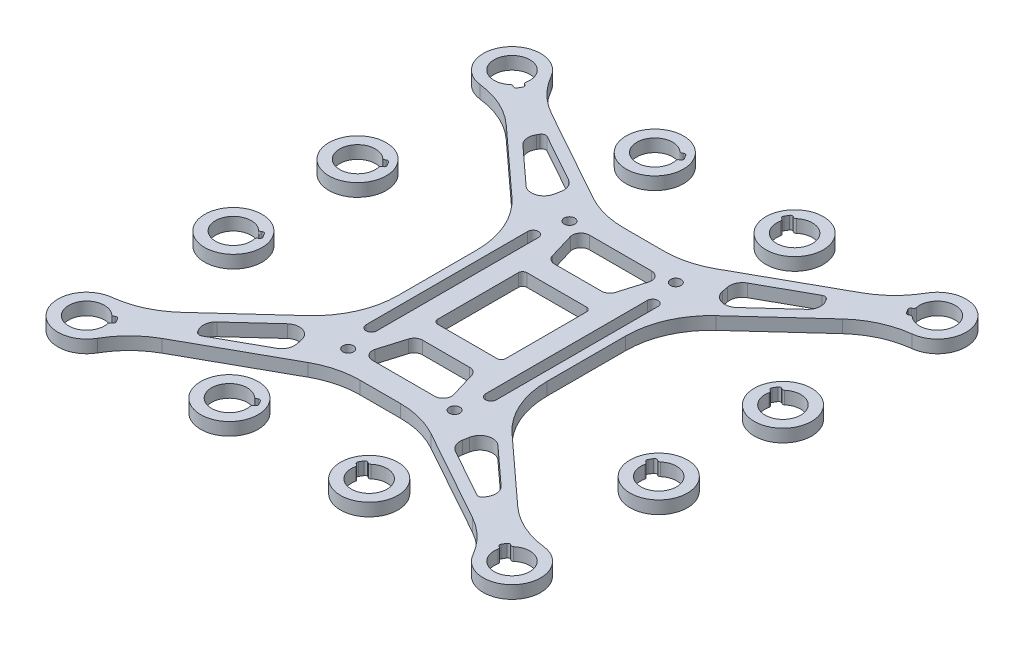
SolidWorks part; units mm, degrees
ref_plane "Front Plane" through (0, 0, 0) normal (0, 0, 1) x (1, 0, 0)
ref_plane "Top Plane" through (0, 0, 0) normal (0, 1, 0) x (1, 0, 0)
ref_plane "Right Plane" through (0, 0, 0) normal (1, 0, 0) x (0, 0, -1)
sketch "Sketch1" plane through (0, 0, 0) normal (0, 1, 0) x (1, 0, 0)
  line L0 (17.5, 31) -> (50, 50) construction
  line L1 (-50, 50) -> (50, 50) construction
  line L2 (-50, 50) -> (-50, -50) construction
  line L3 (-50, -50) -> (50, -50) construction
  line L4 (50, 50) -> (50, -50) construction
  line L5 (0, -50) -> (0, 50) construction
  line L6 (-50, 0) -> (50, 0) construction
  line L7 (-17.5, 31) -> (17.5, 31) construction
  line L8 (-17.5, 31) -> (-17.5, -31) construction
  line L9 (-17.5, -31) -> (17.5, -31) construction
  line L10 (17.5, 31) -> (17.5, -31) construction
  line L11 (0, -31) -> (0, 31) construction
  line L12 (-17.5, 0) -> (17.5, 0) construction
  line L13 (50, -50) -> (17.5, -31) construction
  line L14 (24.0097, -23.9982) -> (39.5398, -38.1874)
  line L15 (14.4627, -33.5209) -> (36.4779, -45.7634)
  line L16 (17.5, -18.0505) -> (9.9296, -31) construction
  line L17 (46.294, -44.3584) -> (43.2658, -49.5381) construction
  line L18 (17.5, -31) -> (11.8579, -27.7015) construction
  line L19 (-4.7426, -31) -> (4.7426, -31)
  line L20 (17.5, -9.233) -> (17.5, 9.233)
  line L21 (24.0097, 23.9982) -> (39.5398, 38.1874)
  line L22 (14.4627, 33.5209) -> (36.4779, 45.7634)
  line L23 (-4.7426, 31) -> (4.7426, 31)
  line L24 (-14.4627, 33.5209) -> (-36.4779, 45.7634)
  line L25 (-24.0097, 23.9982) -> (-39.5398, 38.1874)
  line L26 (-17.5, -9.233) -> (-17.5, 9.233)
  line L27 (-24.0097, -23.9982) -> (-39.5398, -38.1874)
  line L28 (-14.4627, -33.5209) -> (-36.4779, -45.7634)
  line L29 (-14.05, 19) -> (-14.05, -19) construction
  line L30 (-15.3, -28.5) -> (15.3, -28.5) construction
  line L31 (-15.3, -28.5) -> (-15.3, 28.5) construction
  line L32 (-15.3, 28.5) -> (15.3, 28.5) construction
  line L33 (15.3, -28.5) -> (15.3, 28.5) construction
  line L34 (0, 28.5) -> (0, -28.5) construction
  line L35 (-15.3, 0) -> (15.3, 0) construction
  line L36 (-12.8, 19) -> (-12.8, -19)
  line L37 (-15.3, 19) -> (-15.3, -19)
  line L38 (14.05, 19) -> (14.05, -19) construction
  line L39 (-7, -10.5) -> (7, -10.5)
  line L40 (-8, -9.5) -> (-8, 9.5)
  line L41 (-7, 10.5) -> (7, 10.5)
  line L42 (8, -9.5) -> (8, 9.5)
  line L43 (0, 10.5) -> (0, -10.5) construction
  line L44 (-8, 0) -> (8, 0) construction
  line L45 (12.8, 19) -> (12.8, -19)
  line L46 (15.3, 19) -> (15.3, -19)
  line L47 (21.0169, -34.3051) -> (32.3084, -40.5842)
  line L48 (33.6577, -40.215) -> (33.9641, -39.6909)
  line L49 (33.3978, -35.962) -> (24.7539, -28.0645)
  line L50 (19.7788, -29.7423) -> (19.5234, -31.1462)
  line L51 (19.7788, 29.7423) -> (19.5234, 31.1462)
  line L52 (33.3978, 35.962) -> (24.7539, 28.0645)
  line L53 (33.6577, 40.215) -> (33.9641, 39.6909)
  line L54 (21.0169, 34.3051) -> (32.3084, 40.5842)
  line L55 (-33.6577, -40.215) -> (-33.9641, -39.6909)
  line L56 (-21.0169, -34.3051) -> (-32.3084, -40.5842)
  line L57 (-33.3978, -35.962) -> (-24.7539, -28.0645)
  line L58 (-19.7788, -29.7423) -> (-19.5234, -31.1462)
  line L59 (-19.7788, 29.7423) -> (-19.5234, 31.1462)
  line L60 (-33.3978, 35.962) -> (-24.7539, 28.0645)
  line L61 (-33.6577, 40.215) -> (-33.9641, 39.6909)
  line L62 (-21.0169, 34.3051) -> (-32.3084, 40.5842)
  line L63 (-5.5119, 15.5) -> (5.5119, 15.5)
  line L64 (7.4276, 16.9253) -> (9.2276, 22.9253)
  line L65 (7.3119, 25.5) -> (-7.3119, 25.5)
  line L66 (-7.4276, 16.9253) -> (-9.2276, 22.9253)
  line L67 (-7.4276, -16.9253) -> (-9.2276, -22.9253)
  line L68 (7.4276, -16.9253) -> (9.2276, -22.9253)
  line L69 (7.3119, -25.5) -> (-7.3119, -25.5)
  line L70 (-5.5119, -15.5) -> (5.5119, -15.5)
  line L71 (45.7632, -46.9439) -> (45.2585, -47.8072)
  line L72 (46.4472, -46.7646) -> (46.6594, -46.8887)
  line L73 (45.4378, -48.4912) -> (45.65, -48.6153)
  line L74 (-45.7632, -46.9439) -> (-45.2585, -47.8072)
  line L75 (-45.4378, -48.4912) -> (-45.65, -48.6153)
  line L76 (-46.4472, -46.7646) -> (-46.6594, -46.8887)
  line L77 (45.7632, 46.9439) -> (45.2585, 47.8072)
  line L78 (45.4378, 48.4912) -> (45.65, 48.6153)
  line L79 (46.4472, 46.7646) -> (46.6594, 46.8887)
  line L80 (-45.7632, 46.9439) -> (-45.2585, 47.8072)
  line L81 (-46.4472, 46.7646) -> (-46.6594, 46.8887)
  line L82 (-45.4378, 48.4912) -> (-45.65, 48.6153)
  line L83 (46.4472, -12.2646) -> (46.6594, -12.3887)
  line L84 (45.7632, -12.4439) -> (45.2585, -13.3072)
  line L85 (45.4378, -13.9912) -> (45.65, -14.1153)
  line L86 (45.7632, 16.7469) -> (45.2585, 15.8836)
  line L87 (45.4378, 15.1996) -> (45.65, 15.0756)
  line L88 (46.4472, 16.9262) -> (46.6594, 16.8022)
  line L89 (-45.4378, -13.9912) -> (-45.65, -14.1153)
  line L90 (-45.7632, -12.4439) -> (-45.2585, -13.3072)
  line L91 (-46.4472, -12.2646) -> (-46.6594, -12.3887)
  line L92 (-46.4472, 16.9262) -> (-46.6594, 16.8022)
  line L93 (-45.4378, 15.1996) -> (-45.65, 15.0756)
  line L94 (-45.7632, 16.7469) -> (-45.2585, 15.8836)
  line L95 (12.1942, 53.0561) -> (11.6896, 52.1928)
  line L96 (12.8782, 53.2354) -> (13.0904, 53.1113)
  line L97 (11.8689, 51.5088) -> (12.081, 51.3847)
  line L98 (12.1942, -46.9439) -> (11.6896, -47.8072)
  line L99 (11.8689, -48.4912) -> (12.081, -48.6153)
  line L100 (12.8782, -46.7646) -> (13.0904, -46.8887)
  line L101 (-12.8782, -46.7646) -> (-13.0904, -46.8887)
  line L102 (-11.8689, -48.4912) -> (-12.081, -48.6153)
  line L103 (-12.1942, -46.9439) -> (-11.6896, -47.8072)
  line L104 (-11.8689, 51.5088) -> (-12.081, 51.3847)
  line L105 (-12.8782, 53.2354) -> (-13.0904, 53.1113)
  line L106 (-12.1942, 53.0561) -> (-11.6896, 52.1928)
  arc A0 (44.1352, -53.3416) -> (50.7646, -43.2934) centre (50, -50) ccw
  arc A1 (45.8873, -49.1483) -> (47.2403, -46.8339) centre (50, -50) ccw
  arc A2 (45.8873, 49.1483) -> (47.2403, 46.8339) centre (50, 50) cw
  arc A3 (24.0097, -23.9982) -> (17.5, -9.233) centre (37.5, -9.233) cw
  arc A4 (-45.8873, -49.1483) -> (-47.2403, -46.8339) centre (-50, -50) cw
  arc A5 (14.4627, -33.5209) -> (4.7426, -31) centre (4.7426, -51) ccw
  arc A6 (-45.8873, 49.1483) -> (-47.2403, 46.8339) centre (-50, 50) ccw
  arc A7 (36.4779, -45.7634) -> (44.1352, -53.3416) centre (26.7579, -63.2426) cw
  circle A8 centre (50, 50) radius 37.5 construction
  arc A9 (39.5398, -38.1874) -> (50.7646, -43.2934) centre (53.0302, -23.4222) ccw
  arc A10 (24.0097, 23.9982) -> (17.5, 9.233) centre (37.5, 9.233) ccw
  arc A11 (39.5398, 38.1874) -> (50.7646, 43.2934) centre (53.0302, 23.4222) cw
  arc A12 (44.1352, 53.3416) -> (50.7646, 43.2934) centre (50, 50) cw
  arc A13 (36.4779, 45.7634) -> (44.1352, 53.3416) centre (26.7579, 63.2426) ccw
  arc A14 (14.4627, 33.5209) -> (4.7426, 31) centre (4.7426, 51) cw
  arc A15 (-14.4627, 33.5209) -> (-4.7426, 31) centre (-4.7426, 51) ccw
  arc A16 (-36.4779, 45.7634) -> (-44.1352, 53.3416) centre (-26.7579, 63.2426) cw
  arc A17 (-44.1352, 53.3416) -> (-50.7646, 43.2934) centre (-50, 50) ccw
  arc A18 (-39.5398, 38.1874) -> (-50.7646, 43.2934) centre (-53.0302, 23.4222) ccw
  arc A19 (-24.0097, 23.9982) -> (-17.5, 9.233) centre (-37.5, 9.233) cw
  arc A20 (-24.0097, -23.9982) -> (-17.5, -9.233) centre (-37.5, -9.233) ccw
  arc A21 (-39.5398, -38.1874) -> (-50.7646, -43.2934) centre (-53.0302, -23.4222) cw
  arc A22 (-44.1352, -53.3416) -> (-50.7646, -43.2934) centre (-50, -50) cw
  arc A23 (-36.4779, -45.7634) -> (-44.1352, -53.3416) centre (-26.7579, -63.2426) ccw
  arc A24 (-14.4627, -33.5209) -> (-4.7426, -31) centre (-4.7426, -51) cw
  circle A25 centre (-12.5, 26) radius 1.25
  circle A26 centre (12.5, 26) radius 1.25
  circle A27 centre (12.5, -26) radius 1.25
  circle A28 centre (-12.5, -26) radius 1.25
  arc A29 (-12.8, 19) -> (-15.3, 19) centre (-14.05, 19) ccw
  arc A30 (-15.3, -19) -> (-12.8, -19) centre (-14.05, -19) ccw
  arc A31 (12.8, 19) -> (15.3, 19) centre (14.05, 19) cw
  arc A32 (15.3, -19) -> (12.8, -19) centre (14.05, -19) cw
  arc A33 (33.9641, -39.6909) -> (33.3978, -35.962) centre (31.3742, -38.1768) ccw
  arc A34 (21.0169, -34.3051) -> (19.5234, -31.1462) centre (22.475, -31.6832) cw
  arc A35 (24.7539, -28.0645) -> (19.7788, -29.7423) centre (22.7304, -30.2793) ccw
  arc A36 (32.3084, -40.5842) -> (33.6577, -40.215) centre (32.7944, -39.7103) ccw
  arc A37 (21.0169, 34.3051) -> (19.5234, 31.1462) centre (22.475, 31.6832) ccw
  arc A38 (24.7539, 28.0645) -> (19.7788, 29.7423) centre (22.7304, 30.2793) cw
  arc A39 (33.9641, 39.6909) -> (33.3978, 35.962) centre (31.3742, 38.1768) cw
  arc A40 (32.3084, 40.5842) -> (33.6577, 40.215) centre (32.7944, 39.7103) cw
  arc A41 (-33.9641, -39.6909) -> (-33.3978, -35.962) centre (-31.3742, -38.1768) cw
  arc A42 (-32.3084, -40.5842) -> (-33.6577, -40.215) centre (-32.7944, -39.7103) cw
  arc A43 (-21.0169, -34.3051) -> (-19.5234, -31.1462) centre (-22.475, -31.6832) ccw
  arc A44 (-24.7539, -28.0645) -> (-19.7788, -29.7423) centre (-22.7304, -30.2793) cw
  arc A45 (-21.0169, 34.3051) -> (-19.5234, 31.1462) centre (-22.475, 31.6832) cw
  arc A46 (-24.7539, 28.0645) -> (-19.7788, 29.7423) centre (-22.7304, 30.2793) ccw
  arc A47 (-33.9641, 39.6909) -> (-33.3978, 35.962) centre (-31.3742, 38.1768) ccw
  arc A48 (-32.3084, 40.5842) -> (-33.6577, 40.215) centre (-32.7944, 39.7103) ccw
  arc A49 (-7.4276, 16.9253) -> (-5.5119, 15.5) centre (-5.5119, 17.5) ccw
  arc A50 (5.5119, 15.5) -> (7.4276, 16.9253) centre (5.5119, 17.5) ccw
  arc A51 (9.2276, 22.9253) -> (7.3119, 25.5) centre (7.3119, 23.5) ccw
  arc A52 (-9.2276, 22.9253) -> (-7.3119, 25.5) centre (-7.3119, 23.5) cw
  arc A53 (-7, -10.5) -> (-8, -9.5) centre (-7, -9.5) cw
  arc A54 (7, -10.5) -> (8, -9.5) centre (7, -9.5) ccw
  arc A55 (7, 10.5) -> (8, 9.5) centre (7, 9.5) cw
  arc A56 (-8, 9.5) -> (-7, 10.5) centre (-7, 9.5) cw
  arc A57 (5.5119, -15.5) -> (7.4276, -16.9253) centre (5.5119, -17.5) cw
  arc A58 (-7.4276, -16.9253) -> (-5.5119, -15.5) centre (-5.5119, -17.5) cw
  arc A59 (-9.2276, -22.9253) -> (-7.3119, -25.5) centre (-7.3119, -23.5) ccw
  arc A60 (9.2276, -22.9253) -> (7.3119, -25.5) centre (7.3119, -23.5) cw
  arc A61 (-45.2585, -47.8072) -> (-45.4378, -48.4912) centre (-45.6902, -48.0596) cw
  arc A62 (-45.7632, -46.9439) -> (-46.4472, -46.7646) centre (-46.1949, -47.1963) ccw
  arc A63 (-46.6594, -46.8887) -> (-47.2403, -46.8339) centre (-46.9117, -46.457) cw
  arc A64 (-45.65, -48.6153) -> (-45.8873, -49.1483) centre (-45.3976, -49.0469) ccw
  arc A65 (45.65, -48.6153) -> (45.8873, -49.1483) centre (45.3976, -49.0469) cw
  arc A66 (45.2585, -47.8072) -> (45.4378, -48.4912) centre (45.6902, -48.0596) ccw
  arc A67 (45.7632, -46.9439) -> (46.4472, -46.7646) centre (46.1949, -47.1963) cw
  arc A68 (46.6594, -46.8887) -> (47.2403, -46.8339) centre (46.9117, -46.457) ccw
  arc A69 (45.7632, 46.9439) -> (46.4472, 46.7646) centre (46.1949, 47.1963) ccw
  arc A70 (46.6594, 46.8887) -> (47.2403, 46.8339) centre (46.9117, 46.457) cw
  arc A71 (45.65, 48.6153) -> (45.8873, 49.1483) centre (45.3976, 49.0469) ccw
  arc A72 (45.2585, 47.8072) -> (45.4378, 48.4912) centre (45.6902, 48.0596) cw
  arc A73 (-45.7632, 46.9439) -> (-46.4472, 46.7646) centre (-46.1949, 47.1963) cw
  arc A74 (-46.6594, 46.8887) -> (-47.2403, 46.8339) centre (-46.9117, 46.457) ccw
  arc A75 (-45.65, 48.6153) -> (-45.8873, 49.1483) centre (-45.3976, 49.0469) cw
  arc A76 (-45.2585, 47.8072) -> (-45.4378, 48.4912) centre (-45.6902, 48.0596) ccw
  arc A77 (45.2585, -13.3072) -> (45.4378, -13.9912) centre (45.6902, -13.5596) ccw
  arc A78 (46.6594, -12.3887) -> (47.2403, -12.3339) centre (46.9117, -11.957) ccw
  arc A79 (45.8873, -14.6483) -> (47.2403, -12.3339) centre (50, -15.5) ccw
  arc A80 (45.65, -14.1153) -> (45.8873, -14.6483) centre (45.3976, -14.5469) cw
  arc A81 (45.7632, -12.4439) -> (46.4472, -12.2646) centre (46.1949, -12.6963) cw
  arc A82 (45.65, 15.0756) -> (45.8873, 14.5425) centre (45.3976, 14.6439) cw
  arc A83 (46.6594, 16.8022) -> (47.2403, 16.8569) centre (46.9117, 17.2338) ccw
  arc A84 (45.8873, 14.5425) -> (47.2403, 16.8569) centre (50, 13.6908) ccw
  arc A85 (45.2585, 15.8836) -> (45.4378, 15.1996) centre (45.6902, 15.6313) ccw
  arc A86 (45.7632, 16.7469) -> (46.4472, 16.9262) centre (46.1949, 16.4946) cw
  circle A87 centre (50, -15.5) radius 6.75
  circle A88 centre (50, 13.6908) radius 6.75
  circle A89 centre (-50, -15.5) radius 6.75
  arc A90 (-45.7632, -12.4439) -> (-46.4472, -12.2646) centre (-46.1949, -12.6963) ccw
  arc A91 (-45.65, -14.1153) -> (-45.8873, -14.6483) centre (-45.3976, -14.5469) ccw
  arc A92 (-45.8873, -14.6483) -> (-47.2403, -12.3339) centre (-50, -15.5) cw
  arc A93 (-46.6594, -12.3887) -> (-47.2403, -12.3339) centre (-46.9117, -11.957) cw
  arc A94 (-45.2585, -13.3072) -> (-45.4378, -13.9912) centre (-45.6902, -13.5596) cw
  circle A95 centre (-50, 13.6908) radius 6.75
  arc A96 (-45.7632, 16.7469) -> (-46.4472, 16.9262) centre (-46.1949, 16.4946) ccw
  arc A97 (-45.2585, 15.8836) -> (-45.4378, 15.1996) centre (-45.6902, 15.6313) cw
  arc A98 (-45.8873, 14.5425) -> (-47.2403, 16.8569) centre (-50, 13.6908) cw
  arc A99 (-46.6594, 16.8022) -> (-47.2403, 16.8569) centre (-46.9117, 17.2338) cw
  arc A100 (-45.65, 15.0756) -> (-45.8873, 14.5425) centre (-45.3976, 14.6439) ccw
  arc A101 (12.3183, 50.8517) -> (13.6713, 53.1661) centre (16.431, 50) ccw
  arc A102 (13.0904, 53.1113) -> (13.6713, 53.1661) centre (13.3428, 53.543) ccw
  arc A103 (11.6896, 52.1928) -> (11.8689, 51.5088) centre (12.1212, 51.9404) ccw
  circle A104 centre (16.431, 50) radius 6.75
  arc A105 (12.081, 51.3847) -> (12.3183, 50.8517) centre (11.8287, 50.9531) cw
  arc A106 (12.1942, 53.0561) -> (12.8782, 53.2354) centre (12.6259, 52.8037) cw
  arc A107 (12.1942, -46.9439) -> (12.8782, -46.7646) centre (12.6259, -47.1963) cw
  arc A108 (12.081, -48.6153) -> (12.3183, -49.1483) centre (11.8287, -49.0469) cw
  arc A109 (12.3183, -49.1483) -> (13.6713, -46.8339) centre (16.431, -50) ccw
  arc A110 (11.6896, -47.8072) -> (11.8689, -48.4912) centre (12.1212, -48.0596) ccw
  circle A111 centre (16.431, -50) radius 6.75
  arc A112 (13.0904, -46.8887) -> (13.6713, -46.8339) centre (13.3428, -46.457) ccw
  arc A113 (-13.0904, -46.8887) -> (-13.6713, -46.8339) centre (-13.3428, -46.457) cw
  circle A114 centre (-16.431, -50) radius 6.75
  arc A115 (-11.6896, -47.8072) -> (-11.8689, -48.4912) centre (-12.1212, -48.0596) cw
  arc A116 (-12.3183, -49.1483) -> (-13.6713, -46.8339) centre (-16.431, -50) cw
  arc A117 (-12.081, -48.6153) -> (-12.3183, -49.1483) centre (-11.8287, -49.0469) ccw
  arc A118 (-12.1942, -46.9439) -> (-12.8782, -46.7646) centre (-12.6259, -47.1963) ccw
  arc A119 (-12.1942, 53.0561) -> (-12.8782, 53.2354) centre (-12.6259, 52.8037) ccw
  arc A120 (-12.081, 51.3847) -> (-12.3183, 50.8517) centre (-11.8287, 50.9531) ccw
  circle A121 centre (-16.431, 50) radius 6.75
  arc A122 (-11.6896, 52.1928) -> (-11.8689, 51.5088) centre (-12.1212, 51.9404) cw
  arc A123 (-13.0904, 53.1113) -> (-13.6713, 53.1661) centre (-13.3428, 53.543) cw
  arc A124 (-12.3183, 50.8517) -> (-13.6713, 53.1661) centre (-16.431, 50) cw
  point P0 (0, 0)
  point P8 (-45.0062, -48.2389)
  point P12 (0, 0)
  point P66 (0, 0)
  point P80 (-14.05, 0)
  point P85 (0, 0)
  point P96 (14.05, 0)
  point P109 (19.1387, -33.2606)
  point P112 (20.7497, -24.406)
  point P151 (0, 25.5)
  point P163 (0, 15.5)
  point P165 (-7, 15.5)
  point P168 (7, 15.5)
  point P171 (10, 25.5)
  point P174 (-10, 25.5)
  point P177 (-8, -10.5)
  point P180 (8, -10.5)
  point P186 (-8, 10.5)
  point P205 (45.5109, -47.3756)
  point P221 (-46.0156, -46.5123)
  point P224 (-46.9831, -47.0779)
  point P227 (-45.9737, -48.8045)
  point P230 (45.9737, -48.8045)
  point P233 (45.0062, -48.2389)
  point P236 (46.0156, -46.5123)
  point P239 (46.9831, -47.0779)
  point P242 (46.0156, 46.5123)
  point P245 (46.9831, 47.0779)
  point P248 (45.9737, 48.8045)
  point P251 (45.0062, 48.2389)
  point P254 (-46.0156, 46.5123)
  point P257 (-46.9831, 47.0779)
  point P260 (-45.9737, 48.8045)
  point P263 (-45.0062, 48.2389)
  dimension "D3" = 13.5
  dimension "D4" = 8.4
  dimension "D7" = 15
  dimension "D10" = 75
  dimension "D11" = 30.6
  dimension "D12" = 57
  dimension "D13" = 2.5
  dimension "D14" = 12.5
  dimension "D9" = 20
  dimension "D25" = 3
  dimension "D26" = 1
  dimension "D31" = 2
  dimension "D32" = 1
  dimension "D34" = 5.2
  dimension "D35" = 0.5
  dimension "D36" = 13.5
  dimension "D37" = 13.5
  dimension "D38" = 13.5
  dimension "D1" = 100
  dimension "D2" = 100
  dimension "D5" = 35
  dimension "D6" = 62
  dimension "D8" = 6
  dimension "D15" = 26
  dimension "D16" = 38
  dimension "D17" = 2.5
  dimension "D18" = 21
  dimension "D19" = 16
  dimension "D20" = 2.5
  dimension "D21" = 2.5
  dimension "D22" = 13
  dimension "D23" = 70
  dimension "D24" = 9
  dimension "D27" = 10
  dimension "D28" = 7
  dimension "D29" = 10
  dimension "D30" = 5
  dimension "D33" = 2
extrude "Boss-Extrude2" add sketch "Sketch1" along normal blind 3
